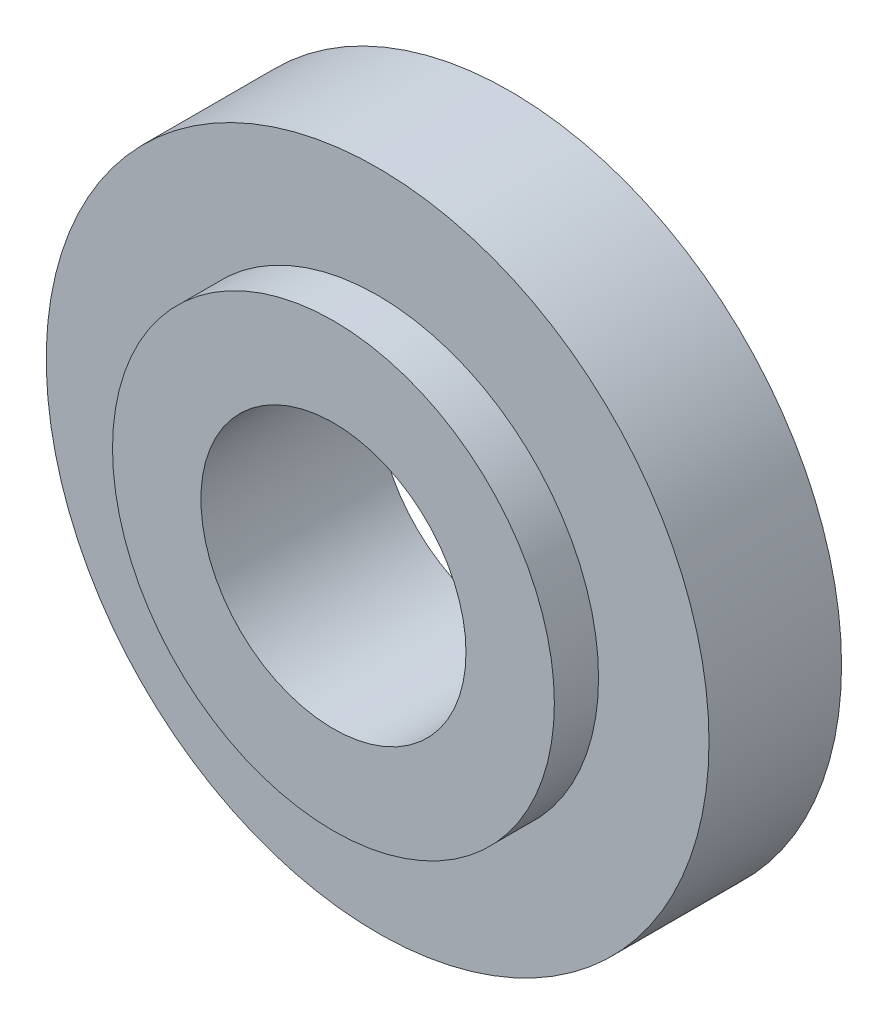
SolidWorks part; units mm, degrees
ref_plane "Ön Düzlem" through (0, 0, 0) normal (0, 0, 1) x (1, 0, 0)
ref_plane "Üst Düzlem" through (0, 0, 0) normal (0, 1, 0) x (1, 0, 0)
ref_plane "Sağ Düzlem" through (0, 0, 0) normal (1, 0, 0) x (0, 0, -1)
sketch "Çizim1" plane through (0, 0, 0) normal (0, 0, 1) x (1, 0, 0)
  circle A0 centre (0, 0) radius 3.75
  dimension "D1" = 7.5
extrude "Yükseklik-Ekstrüzyon1" add sketch "Çizim1" along normal blind 1.5
sketch "Çizim2" plane through (0, 0, 1.5) normal (0, 0, 1) x (1, 0, 0)
  circle A0 centre (0, 0) radius 2.5
  dimension "D1" = 5
extrude "Yükseklik-Ekstrüzyon2" add sketch "Çizim2" along normal blind 0.5
sketch "Çizim3" plane through (0, 0, 2) normal (0, 0, 1) x (1, 0, 0)
  circle A0 centre (0, 0) radius 1.5
extrude "Kes-Ekstrüzyon1" cut sketch "Çizim3" against normal blind 4.5
